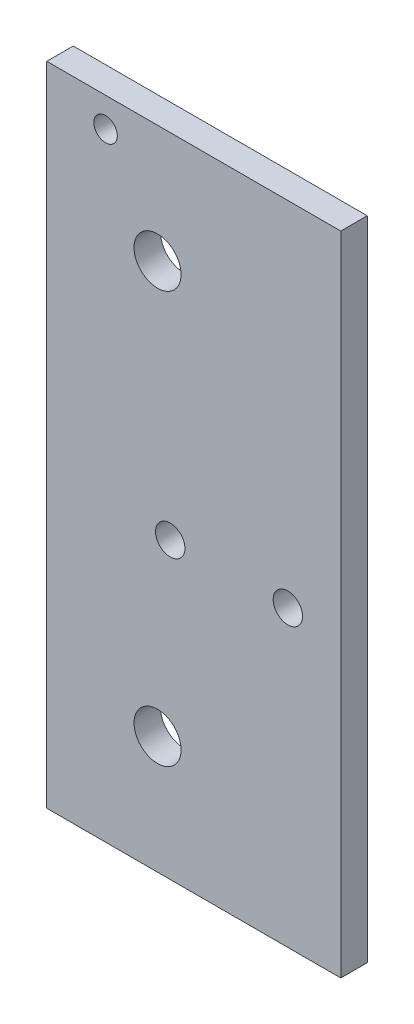
SolidWorks part; units mm, degrees
ref_plane "Front Plane" through (0, 0, 0) normal (0, 0, 1) x (1, 0, 0)
ref_plane "Top Plane" through (0, 0, 0) normal (0, 1, 0) x (1, 0, 0)
ref_plane "Right Plane" through (0, 0, 0) normal (1, 0, 0) x (0, 0, -1)
sketch "Sketch1" plane through (0, 0, 0) normal (0, 0, 1) x (1, 0, 0)
  line L1 (0, 0) -> (50, 0)
  line L2 (0, 0) -> (0, 110)
  line L3 (0, 110) -> (50, 110)
  line L4 (50, 0) -> (50, 110)
  dimension "D1" = 110
  dimension "D2" = 50
extrude "Boss-Extrude1" add sketch "Sketch1" along normal blind 4.5
sketch "Sketch2" plane through (0, 0, 4.5) normal (0, 0, 1) x (1, 0, 0)
  line L0 (50, 110) -> (0, 110) construction
  line L1 (0, 110) -> (0, 0) construction
  circle A0 centre (18.84, 90) radius 4
  circle A1 centre (18.84, 20) radius 4
  dimension "D1" = 8
  dimension "D4" = 8
  dimension "D2" = 20
  dimension "D3" = 18.84
  dimension "D5" = 70
extrude "Cut-Extrude1" cut sketch "Sketch2" against normal blind 4.5
sketch "Sketch3" plane through (0, 0, 4.5) normal (0, 0, 1) x (1, 0, 0)
  line L0 (50, 0) -> (50, 110) construction
  line L1 (0, 0) -> (50, 0) construction
  circle A0 centre (41, 50) radius 2.5
  circle A1 centre (21, 50) radius 2.5
  dimension "D1" = 5
  dimension "D5" = 5
  dimension "D2" = 9
  dimension "D3" = 50
  dimension "D4" = 20
extrude "Cut-Extrude2" cut sketch "Sketch3" against normal blind 4.5
sketch "Sketch6" plane through (0, 0, 4.5) normal (0, 0, 1) x (1, 0, 0)
  circle A0 centre (10, 105) radius 2
extrude "Cut-Extrude3" cut sketch "Sketch6" against normal blind 10 contours A0
